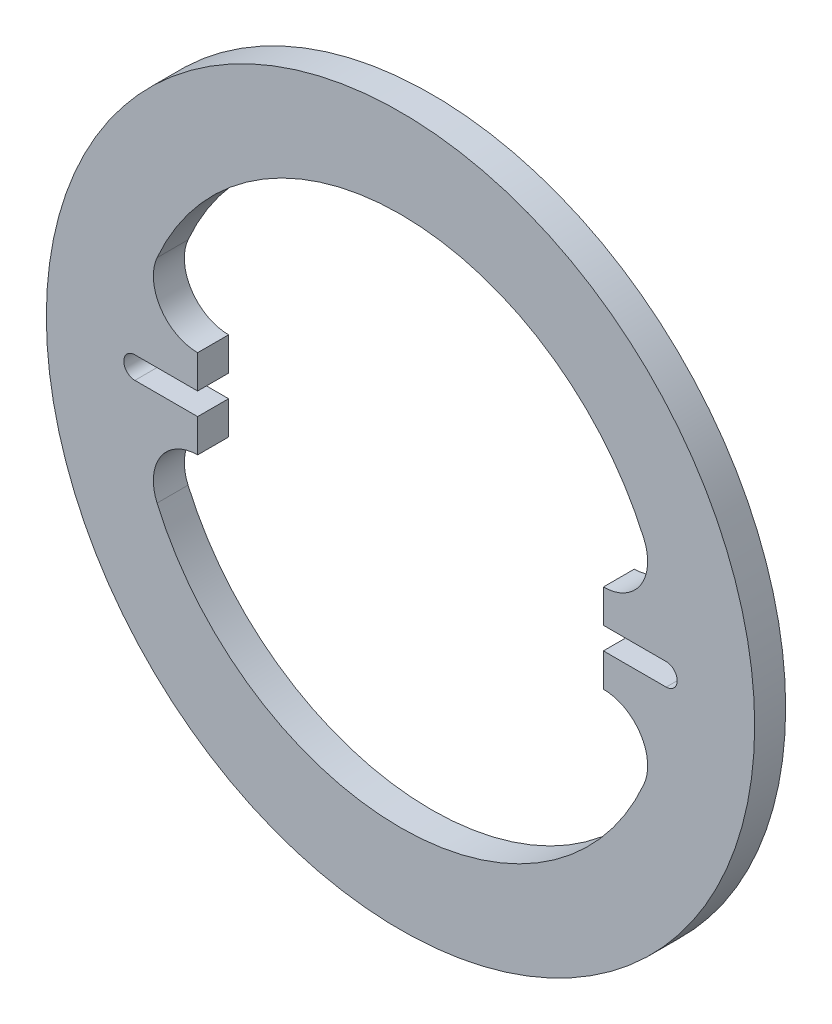
SolidWorks part; units mm, degrees
ref_plane "Front Plane" through (0, 0, 0) normal (0, 0, 1) x (1, 0, 0)
ref_plane "Top Plane" through (0, 0, 0) normal (0, 1, 0) x (1, 0, 0)
ref_plane "Right Plane" through (0, 0, 0) normal (1, 0, 0) x (0, 0, -1)
sketch "Sketch1" plane through (0, 0, 0) normal (0, 0, 1) x (1, 0, 0)
  circle A0 centre (0, 0) radius 101.6
  dimension "D1" = 203.2
extrude "Boss-Extrude1" add sketch "Sketch1" along normal blind 8.89
sketch "Sketch2" plane through (0, 0, 8.89) normal (0, 0, 1) x (1, 0, 0)
  circle A0 centre (0, 0) radius 25.4
  dimension "D1" = 50.8
extrude "Cut-Extrude1" cut sketch "Sketch2" against normal through all
sketch "Sketch3" plane through (0, 0, 8.89) normal (0, 0, 1) x (1, 0, 0)
  line L0 (0, 0) -> (0, 63.5) construction
  line L1 (58.1987, 25.4) -> (-58.1987, 25.4) construction
  circle A0 centre (0, 0) radius 63.5 construction
  arc A1 (-58.1987, 25.4) -> (58.1987, 25.4) centre (0, 0) cw construction
  arc A2 (69.8385, 30.48) -> (-69.8385, 30.48) centre (0, 0) ccw
  arc A3 (46.559, 20.32) -> (-46.559, 20.32) centre (0, 0) ccw
  arc A4 (46.559, 20.32) -> (69.8385, 30.48) centre (58.1987, 25.4) ccw
  arc A5 (-69.8385, 30.48) -> (-46.559, 20.32) centre (-58.1987, 25.4) ccw
  point P5 (0, 63.5)
  dimension "D1" = 127
  dimension "D2" = 25.4
  dimension "D3" = 12.7
extrude "Cut-Extrude2" cut sketch "Sketch3" against normal through all
mirror "Mirror1" about plane through (0, 0, 0) normal (0, 1, 0) of "Cut-Extrude2"
sketch "Sketch4" plane through (0, 0, 8.89) normal (0, 0, 1) x (1, 0, 0)
  line L0 (101.6, 0) -> (-101.6, 0) construction
  line L1 (0, 101.6) -> (0, -101.6) construction
  line L2 (76.2, 0) -> (25.4, 0) construction
  line L3 (-76.2, 0) -> (-25.4, 0) construction
  line L4 (76.2, -3.175) -> (25.4, -3.175)
  line L5 (76.2, 3.175) -> (25.4, 3.175)
  line L6 (-76.2, -3.175) -> (-25.4, -3.175)
  line L7 (-76.2, 3.175) -> (-25.4, 3.175)
  circle A0 centre (0, 0) radius 101.6 construction
  arc A1 (76.2, -3.175) -> (76.2, 3.175) centre (76.2, 0) ccw
  arc A2 (25.4, 3.175) -> (25.4, -3.175) centre (25.4, 0) ccw
  arc A3 (-76.2, -3.175) -> (-76.2, 3.175) centre (-76.2, 0) cw
  arc A4 (-25.4, 3.175) -> (-25.4, -3.175) centre (-25.4, 0) cw
  point P11 (50.8, 0)
  point P16 (-50.8, 0)
  dimension "D1" = 50.8
  dimension "D2" = 50.8
  dimension "D3" = 6.35
extrude "Cut-Extrude3" cut sketch "Sketch4" against normal through all
sketch "Sketch6" [suppressed] plane through (0, 0, 8.89) normal (0, 0, 1) x (1, 0, 0)
  line L0 (-101.6, 0) -> (101.6, 0) construction
  line L1 (-92.202, -3.429) -> (92.202, -3.429)
  line L2 (-92.202, -3.429) -> (-92.202, 3.429)
  line L3 (-92.202, 3.429) -> (92.202, 3.429)
  line L4 (92.202, -3.429) -> (92.202, 3.429)
  line L5 (0, 101.6) -> (0, -101.6) construction
  circle A0 centre (0, 0) radius 101.6 construction
  dimension "D1" = 6.858
  dimension "D2" = 184.404
extrude "Cut-Extrude4" [suppressed] cut sketch "Sketch6" against normal through all
sketch "Sketch7" [suppressed] plane through (0, 0, 8.89) normal (0, 0, 1) x (1, 0, 0)
  line L0 (85.852, -41.2553) -> (85.852, 41.2553)
  line L1 (0, 101.6) -> (0, -101.6) construction
  line L2 (92.202, -3.429) -> (92.202, 3.429) construction
  line L3 (-85.852, -41.2553) -> (-85.852, 41.2553)
  arc A0 (85.852, 41.2553) -> (-85.852, 41.2553) centre (0, 0) ccw
  circle A1 centre (0, 0) radius 101.6 construction
  arc A2 (-85.852, -41.2553) -> (85.852, -41.2553) centre (0, 0) ccw
  dimension "D1" = 6.35
  dimension "D2" = 6.35
extrude "Cut-Extrude5" [suppressed] cut sketch "Sketch7" against normal through all
sketch "Sketch8" [suppressed] plane through (0, 0, 0) normal (0, 0, -1) x (-1, 0, 0)
  line L0 (0, 101.6) -> (0, -101.6) construction
  line L1 (-101.6, 0) -> (101.6, 0) construction
  line L2 (-25.4, 0) -> (25.4, 0) construction
  line L3 (-25.4, 3.302) -> (25.4, 3.302)
  line L4 (-25.4, -3.302) -> (25.4, -3.302)
  line L5 (63.5, 0) -> (88.9, 0) construction
  line L6 (63.5, 3.302) -> (88.9, 3.302)
  line L7 (63.5, -3.302) -> (88.9, -3.302)
  line L8 (-63.5, 0) -> (-88.9, 0) construction
  line L9 (-63.5, 3.302) -> (-88.9, 3.302)
  line L10 (-63.5, -3.302) -> (-88.9, -3.302)
  circle A0 centre (0, 0) radius 101.6 construction
  arc A1 (-25.4, 3.302) -> (-25.4, -3.302) centre (-25.4, 0) ccw
  arc A2 (25.4, -3.302) -> (25.4, 3.302) centre (25.4, 0) ccw
  arc A3 (63.5, 3.302) -> (63.5, -3.302) centre (63.5, 0) ccw
  arc A4 (88.9, -3.302) -> (88.9, 3.302) centre (88.9, 0) ccw
  arc A5 (-63.5, 3.302) -> (-63.5, -3.302) centre (-63.5, 0) cw
  arc A6 (-88.9, -3.302) -> (-88.9, 3.302) centre (-88.9, 0) cw
  point P9 (0, 0)
  point P17 (76.2, 0)
  point P24 (-76.2, 0)
  dimension "D1" = 50.8
  dimension "D2" = 6.604
  dimension "D3" = 25.4
  dimension "D4" = 25.4
extrude "Cut-Extrude6" [suppressed] cut sketch "Sketch8" against normal through all
sketch "Sketch9" [suppressed] plane through (0, 0, 6.35) normal (0, 0, 1) x (1, 0, 0)
  line L0 (-101.6, 0) -> (101.6, 0) construction
  line L1 (0, 101.6) -> (0, -101.6) construction
  circle A0 centre (0, 0) radius 101.6 construction
  circle A1 centre (47.498, 0) radius 2.54
  circle A2 centre (-47.498, 0) radius 2.54
  dimension "D1" = 5.08
  dimension "D2" = 94.996
extrude "Cut-Extrude7" [suppressed] cut sketch "Sketch9" against normal through all
sketch "Sketch10" [suppressed] plane through (0, 0, 6.35) normal (0, 0, 1) x (1, 0, 0)
  line L5 (-14.986, -19.558) -> (14.986, -19.558)
  line L6 (-14.986, -19.558) -> (-14.986, -14.478)
  line L7 (-14.986, -14.478) -> (14.986, -14.478)
  line L8 (14.986, -19.558) -> (14.986, -14.478)
  point P4 (0, -14.478)
  dimension "D1" = 5.08
  dimension "D2" = 29.972
  dimension "D3" = 14.478
extrude "Boss-Extrude2" [suppressed] add sketch "Sketch10" along normal blind 25.908
sketch "Sketch11" [suppressed] plane through (14.986, 0, 0) normal (1, 0, 0) x (0, 0, -1)
  line L0 (-32.258, -19.558) -> (-6.35, -34.516)
  line L1 (-6.35, 101.6) -> (-6.35, -101.6) construction
  line L2 (-6.35, -34.516) -> (-6.35, -19.558)
  line L3 (-6.35, -19.558) -> (-32.258, -19.558)
  dimension "D1" = 30
extrude "Boss-Extrude3" [suppressed] add sketch "Sketch11" against normal blind 5.08
ref_plane "Plane1" [suppressed] through (0, 0, 0) normal (1, 0, 0) x (0, 0, -1)
mirror "Mirror2" [suppressed] about plane through (0, 0, 0) normal (1, 0, 0)
sketch "Sketch12" [suppressed] plane through (0, -14.478, 0) normal (0, 1, 0) x (1, 0, 0)
  line L0 (14.986, -32.258) -> (-14.986, -32.258) construction
  circle A0 centre (0, -16.51) radius 3.937
  dimension "D1" = 7.874
  dimension "D2" = 15.748
extrude "Cut-Extrude8" [suppressed] cut sketch "Sketch12" against normal through all
sketch "Sketch13" [suppressed] plane through (0, 0, 6.35) normal (0, 0, 1) x (1, 0, 0)
  line L0 (-100.8031, 12.7) -> (100.8031, 12.7) construction
  line L1 (-91.836, 12.7) -> (91.836, 12.7)
  circle A0 centre (0, 0) radius 101.6 construction
  arc A1 (-69.8385, 30.48) -> (-46.559, 20.32) centre (-58.1987, 25.4) ccw construction
  arc A2 (-91.836, 12.7) -> (91.836, 12.7) centre (0, 0) cw
  dimension "D1" = 8.89
extrude "Cut-Extrude9" [suppressed] cut sketch "Sketch13" against normal through all
sketch "Sketch14" plane through (0, 0, 8.89) normal (0, 0, 1) x (1, 0, 0)
  line L0 (-58.1987, -12.7) -> (-58.1987, 12.7)
  line L1 (58.1987, 12.7) -> (58.1987, -12.7)
  arc A0 (-46.559, -20.32) -> (-69.8385, -30.48) centre (-58.1987, -25.4) ccw construction
  arc A1 (-69.8385, 30.48) -> (-46.559, 20.32) centre (-58.1987, 25.4) ccw construction
  arc A2 (46.559, 20.32) -> (69.8385, 30.48) centre (58.1987, 25.4) ccw construction
  arc A3 (69.8385, -30.48) -> (46.559, -20.32) centre (58.1987, -25.4) ccw construction
  arc A4 (46.559, 20.32) -> (-46.559, 20.32) centre (0, 0) ccw construction
  arc A5 (-46.559, -20.32) -> (46.559, -20.32) centre (0, 0) ccw construction
  arc A6 (46.559, 20.32) -> (58.1987, 12.7) centre (58.1987, 25.4) ccw
  arc A7 (58.1987, -12.7) -> (46.559, -20.32) centre (58.1987, -25.4) ccw
  arc A8 (-46.559, -20.32) -> (-58.1987, -12.7) centre (-58.1987, -25.4) ccw
  arc A9 (-58.1987, 12.7) -> (-46.559, 20.32) centre (-58.1987, 25.4) ccw
  arc A10 (46.559, 20.32) -> (-46.559, 20.32) centre (0, 0) ccw
  arc A11 (-46.559, -20.32) -> (46.559, -20.32) centre (0, 0) ccw
extrude "Cut-Extrude10" cut sketch "Sketch14" against normal through all
